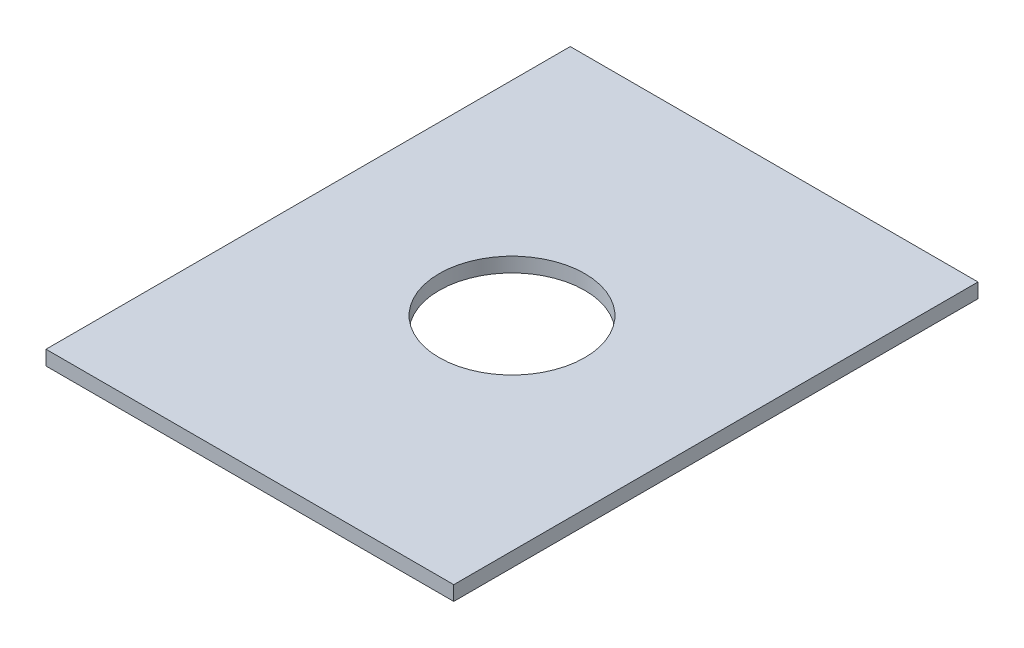
SolidWorks part; units mm, degrees
ref_plane "Front Plane" through (0, 0, 0) normal (0, 0, 1) x (1, 0, 0)
ref_plane "Top Plane" through (0, 0, 0) normal (0, 1, 0) x (1, 0, 0)
ref_plane "Right Plane" through (0, 0, 0) normal (1, 0, 0) x (0, 0, -1)
sketch "Sketch1" plane through (0, 0, 0) normal (0, 1, 0) x (1, 0, 0)
  line L1 (-70, 90) -> (70, 90)
  line L2 (-70, 90) -> (-70, -90)
  line L3 (-70, -90) -> (70, -90)
  line L4 (70, 90) -> (70, -90)
  line L5 (-70, 90) -> (70, -90) construction
  line L6 (-70, -90) -> (70, 90) construction
  point P0 (0, 0)
  dimension "D1" = 140
  dimension "D2" = 180
extrude "Boss-Extrude1" add sketch "Sketch1" along normal blind 5
sketch "Sketch2" plane through (0, 5, 0) normal (0, 1, 0) x (1, 0, 0)
  circle A0 centre (0, 0) radius 25
  dimension "D1" = 50
extrude "Cut-Extrude1" cut sketch "Sketch2" against normal through all
